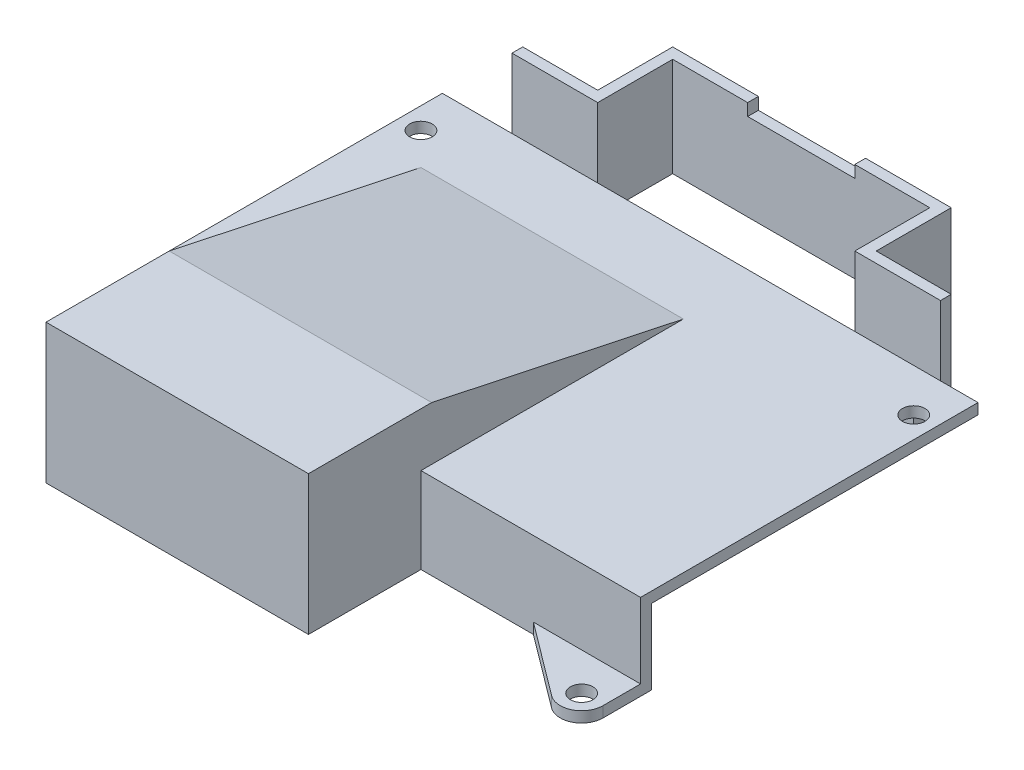
SolidWorks part; units mm, degrees
ref_plane "Alzado" through (0, 0, 0) normal (0, 0, 1) x (1, 0, 0)
ref_plane "Planta" through (0, 0, 0) normal (0, 1, 0) x (1, 0, 0)
ref_plane "Vista lateral" through (0, 0, 0) normal (1, 0, 0) x (0, 0, -1)
sketch "Croquis1" plane through (0, 0, 0) normal (0, 1, 0) x (1, 0, 0)
  line L0 (0, 0) -> (0, -21.0551) construction
  line L1 (50, 8) -> (50, -41)
  line L2 (50, 8) -> (-50, 8)
  line L4 (-50, -41) -> (-40, -41)
  line L8 (-50, 8) -> (-50, -41)
  line L9 (-40, -41) -> (-40, -6)
  line L10 (-40, -6) -> (9, -6)
  line L11 (9, -6) -> (9, -41)
  line L12 (9, -41) -> (50, -41)
  circle A0 centre (46, 0) radius 2.1
  circle A1 centre (-46, 0) radius 2.1
  dimension "D1" = 4.2
  dimension "D2" = 92
  dimension "D3" = 4
  dimension "D4" = 8
  dimension "D5" = 41
  dimension "D6" = 40
  dimension "D7" = 9
  dimension "D8" = 6
extrude "Saliente-Extruir1" add sketch "Croquis1" along normal blind 2
ref_plane "Plano1" through (0, 12, 0) normal (0, 1, 0) x (1, 0, 0)
sketch "Croquis4" plane through (0, 12, 0) normal (0, 1, 0) x (1, 0, 0)
  line L0 (9, -53) -> (9, -76)
  line L1 (9, -76) -> (-40, -76)
  line L2 (-40, -76) -> (-40, -53)
  line L3 (-40, -53) -> (9, -53)
  line L4 (0, 0) -> (-65.2954, 0) construction
  dimension "D1" = 53
  dimension "D2" = 76
  dimension "D3" = 9
  dimension "D4" = 40
extrude "Saliente-Extruir3" add sketch "Croquis4" against normal blind 2 separate body
sketch "Croquis6" plane through (0, 10, 0) normal (0, -1, 0) x (1, 0, 0)
  line L0 (-38, 74) -> (7, 74)
  line L1 (-40, 53) -> (-40, 76) construction
  line L2 (7, 74) -> (7, 53)
  line L4 (9, 53) -> (9, 76)
  line L5 (9, 76) -> (-40, 76)
  line L6 (-40, 76) -> (-40, 53)
  line L9 (7, 53) -> (9, 53)
  line L16 (-40, 53) -> (-38, 53)
  line L17 (-38, 53) -> (-38, 74)
  dimension "D1" = 2
  dimension "D2" = 2
  dimension "D4" = 2
extrude "Saliente-Extruir4" add sketch "Croquis6" along normal blind 24
sketch "Croquis7" plane through (0, 0, 53) normal (0, 0, 1) x (1, 0, 0)
  line L1 (50, 2) -> (50, -14)
  line L2 (50, -14) -> (9, -14)
  line L3 (9, -14) -> (9, 2)
  line L4 (50, 2) -> (50, 0) construction
  line L5 (50, 2) -> (50, 0) construction
  line L6 (9, 2) -> (50, 2) construction
  line L8 (9, -14) -> (9, 12) construction
  line L9 (-50, 2) -> (50, 2)
  line L14 (-40, 2) -> (-50, 2)
  line L15 (-50, 2) -> (-50, -14)
  line L16 (-50, -14) -> (-40, -14)
  line L18 (-40, -14) -> (-40, 2)
  line L19 (9, -14) -> (-40, -14) construction
  line L21 (-50, 2) -> (50, 2) construction
  line L22 (9, -14) -> (9, 12) construction
  line L23 (9, -14) -> (9, 12) construction
extrude "Saliente-Extruir5" add sketch "Croquis7" along normal blind 2
sketch "Croquis8" plane through (0, -14, 0) normal (0, -1, 0) x (1, 0, 0)
  line L0 (50, 55) -> (50, 62)
  line L1 (43.6, 65.2) -> (30, 55)
  line L2 (-40, 55) -> (-40, 76)
  line L4 (30, 55) -> (50, 55)
  line L5 (0, 0) -> (0, 97.664) construction
  line L6 (-40, 55) -> (-50, 55)
  line L8 (-50, 55) -> (-50, 62)
  line L9 (-50, 55) -> (-40, 55) construction
  line L10 (-49.1337, 64.4859) -> (-40, 76)
  line L11 (50, 55) -> (9, 55) construction
  arc A0 (50, 62) -> (43.6, 65.2) centre (46, 62) ccw
  circle A1 centre (46, 62) radius 2.1
  circle A2 centre (46, 0) radius 2.1 construction
  circle A3 centre (46, 0) radius 2.1 construction
  circle A4 centre (-46, 62) radius 2.1
  arc A5 (-50, 62) -> (-49.1337, 64.4859) centre (-46, 62) cw
  dimension "D1" = 4.2
  dimension "D2" = 62
  dimension "D3" = 20
extrude "Saliente-Extruir6" add sketch "Croquis8" against normal blind 2
sketch "Croquis9" plane through (0, 0, 41) normal (0, 0, 1) x (1, 0, 0)
  line L0 (9, 2) -> (9, 12) construction
  line L1 (9, 2) -> (9, 12) construction
  line L2 (-40, 2) -> (-40, 12) construction
  line L3 (-40, 2) -> (-40, 12) construction
  line L4 (-50, 2) -> (-50, 0)
  line L5 (-50, 0) -> (-40, 0)
  line L6 (-50, 0) -> (-40, 0) construction
  line L7 (-40, 0) -> (-40, 2)
  line L8 (-40, 2) -> (-50, 2)
  line L9 (50, 2) -> (50, 0)
  line L10 (50, 0) -> (9, 0)
  line L14 (9, 0) -> (9, 2)
  line L17 (9, 2) -> (50, 2)
  line L18 (50, 2) -> (50, 0) construction
  line M9 (-40, 2) -> (-50, 2)
  line M10 (-50, 2) -> (-50, 0)
  line M11 (-50, 0) -> (-40, 0)
extrude "Saliente-Extruir7" add sketch "Croquis9" along normal up to surface (12 mm away) contours L17 L14 L10 L9 | L7 M11 M9 M10 up to face at (-10.3333, -0.3333, 53)
sketch "Croquis12" plane through (9, 0, 0) normal (-1, 0, 0) x (0, 0, 1)
  line L0 (53, 10) -> (53, 12)
  line L1 (53, 2) -> (53, 12) construction
  line L2 (53, 12) -> (6, 2)
  line L3 (6, 2) -> (6, 0)
  line L6 (6, 0) -> (53, 10)
extrude "Saliente-Extruir8" add sketch "Croquis12" along normal up to surface (49 mm away) up to face at (-40, 0.6667, 61.3333)
sketch "Croquis13" plane through (9, 0, 0) normal (1, 0, 0) x (0, 0, -1)
  line L0 (-53, 12) -> (-53, 0)
  line L2 (-6, 2) -> (-53, 12)
  line L3 (-6, 2) -> (-6, 0)
  line L4 (-6, 0) -> (-53, 0)
extrude "Saliente-Extruir9" add sketch "Croquis13" against normal blind 2
sketch "Croquis14" plane through (-40, 0, 0) normal (1, 0, 0) x (0, 0, -1)
  line L0 (-6, 0) -> (-6, 2)
  line L1 (-6, 2) -> (-53, 10)
  line L2 (-53, 10) -> (-53, 0)
  line L3 (-53, 0) -> (-6, 0)
  line L4 (-53, 12) -> (-6, 2) construction
extrude "Saliente-Extruir10" add sketch "Croquis14" along normal blind 2
sketch "Croquis15" plane through (0, 0, -8) normal (0, 0, -1) x (-1, 0, 0)
  line L0 (-40, -6.5) -> (40, -6.5)
  line L5 (40, -6.5) -> (40, 2)
  line L9 (-40, -6.5) -> (-40, 2)
  line L10 (-40, 2) -> (40, 2)
  line L11 (-50, 0) -> (50, 0) construction
  line L12 (-50, 2) -> (50, 2) construction
  line L14 (0, 0) -> (0, 12.2158) construction
  dimension "D1" = 40
  dimension "D2" = 40
  dimension "D3" = 6.5
extrude "Saliente-Extruir11" add sketch "Croquis15" against normal blind 2
sketch "Croquis16" plane through (0, -6.5, 0) normal (0, -1, 0) x (1, 0, 0)
  line L0 (40, -6) -> (40, -13)
  line L1 (-40, -6) -> (-40, -13)
  line L2 (-40, -13) -> (-26, -13)
  line L3 (40, -6) -> (-40, -6)
  line L4 (24, -11) -> (24, -25)
  line L5 (26, -13) -> (40, -13)
  line L6 (24, -25) -> (-24, -25)
  line L7 (-24, -25) -> (-24, -11)
  line L8 (-26, -13) -> (-26, -27)
  line L9 (-26, -27) -> (26, -27)
  line L10 (26, -27) -> (26, -13)
  line L12 (0, 0) -> (0, -49.3395) construction
  line L13 (24, -11) -> (-24, -11)
  line L14 (46, 0) -> (-46, 0) construction
  dimension "D1" = 13
  dimension "D2" = 24
  dimension "D3" = 24
  dimension "D4" = 2
  dimension "D5" = 2
  dimension "D6" = 2
  dimension "D7" = 25
  dimension "D8" = 11
extrude "Saliente-Extruir12" add sketch "Croquis16" against normal blind 2
sketch "Croquis17" plane through (0, -4.5, 0) normal (0, 1, 0) x (1, 0, 0)
  line L1 (24, 25) -> (-24, 25)
  line L4 (-26, 13) -> (-26, 27)
  line L5 (-26, 27) -> (26, 27)
  line L6 (26, 27) -> (26, 13)
  line L9 (-24, 11) -> (-38.1391, 11)
  line L11 (-38.1391, 11) -> (-40, 11)
  line L13 (-40, 11) -> (-40, 13)
  line L14 (-40, 13) -> (-26, 13)
  line L15 (0, 0) -> (0, 19.8753) construction
  line L16 (40, 13) -> (26, 13)
  line L20 (24, 11) -> (38.1391, 11)
  line L22 (38.1391, 11) -> (40, 11)
  line L23 (40, 13) -> (40, 8) construction
  line L24 (40, 11) -> (40, 13)
  line L26 (-24, 25) -> (-24, 11)
  line L27 (24, 25) -> (24, 11)
  point P0 (38.1391, 11)
  dimension "D1" = 2
  dimension "D3" = 40
extrude "Saliente-Extruir13" add sketch "Croquis17" along normal blind 16.5
sketch "Croquis18" plane through (0, 0, -27) normal (0, 0, -1) x (-1, 0, 0)
  line L0 (-10, 12) -> (-10, 9.75)
  line L1 (-26, 12) -> (26, 12) construction
  line L2 (-10, 9.75) -> (10, 9.75)
  line L3 (10, 9.75) -> (10, 12)
  line L4 (0, 0) -> (0, 18.6965) construction
  dimension "D1" = 20
  dimension "D2" = 2.25
extrude "Cortar-Extruir1" cut sketch "Croquis18" against normal blind 6 and the other way through all
